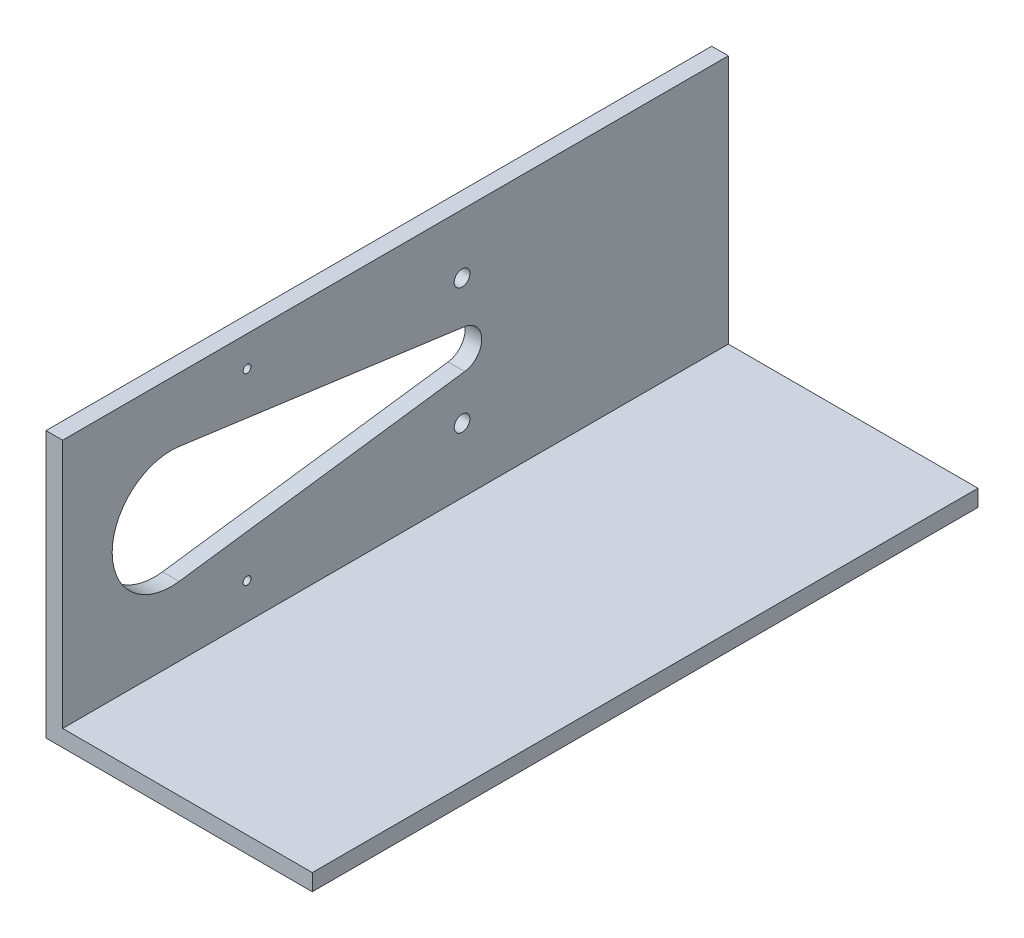
SolidWorks part; units mm, degrees
ref_plane "Alzado" through (0, 0, 0) normal (0, 0, 1) x (1, 0, 0)
ref_plane "Planta" through (0, 0, 0) normal (0, 1, 0) x (1, 0, 0)
ref_plane "Vista lateral" through (0, 0, 0) normal (1, 0, 0) x (0, 0, -1)
sketch "Croquis1" plane through (0, 0, 0) normal (0, 0, 1) x (1, 0, 0)
  line L0 (0, 101.6) -> (0, 0)
  line L1 (0, 0) -> (101.6, 0)
  line L2 (101.6, 0) -> (101.6, 6.35)
  line L3 (101.6, 6.35) -> (6.35, 6.35)
  line L4 (6.35, 6.35) -> (6.35, 101.6)
  line L5 (6.35, 101.6) -> (0, 101.6)
  dimension "D1" = 6.35
  dimension "D2" = 101.6
extrude "Saliente-Extruir1" add sketch "Croquis1" along normal blind 254
sketch "Croquis2" plane through (0, 0, 0) normal (-1, 0, 0) x (0, 0, 1)
  line L0 (101.6, 0) -> (101.6, 55) construction
  line L1 (254, 0) -> (0, 0) construction
  line L2 (0, 0) -> (0, -20) construction
  line L3 (0, -20) -> (254, -20) construction
  line L4 (254, -20) -> (254, 0) construction
  line L5 (101.6, 55) -> (212.6, 55) construction
  line L6 (100.5865, 62.4312) -> (209.5595, 77.2936)
  line L7 (100.5865, 47.5688) -> (209.5595, 32.7064)
  line L8 (101.6, 0) -> (101.6, -46.6) construction
  line L9 (101.6, -20) -> (101.6, -46.6) construction
  line L10 (0, 6.35) -> (254, 6.35) construction
  line L11 (0, 101.6) -> (0, 0) construction
  line L12 (254, 101.6) -> (254, 0) construction
  line L13 (183.64, 55) -> (183.64, 90) construction
  line L14 (101.6, 156.6) -> (254, 156.6) construction
  line L15 (254, 156.6) -> (254, -20) construction
  circle A0 centre (101.6, 55) radius 47 construction
  circle A1 centre (101.6, 55) radius 101.6 construction
  circle A2 centre (212.6, 55) radius 22.5
  circle A3 centre (101.6, 55) radius 7.5
  circle A4 centre (183.64, 90) radius 1.5
  circle A5 centre (183.64, 20) radius 1.5
  dimension "D1" = 94
  dimension "D3" = 203.2
  dimension "D6" = 45
  dimension "D7" = 15
  dimension "D12" = 3
  dimension "D2" = 55
  dimension "D4" = 20
  dimension "D5" = 111
  dimension "D8" = 6.35
  dimension "D9" = 101.6
  dimension "D10" = 82.04
  dimension "D11" = 35
extrude "Cortar-Extruir1" cut sketch "Croquis2" against normal blind 254 contours A3 | A3 L7 A2 L6 | A2 | A4 | A5
sketch "Croquis3" plane through (0, 0, 0) normal (-1, 0, 0) x (0, 0, 1)
  line L0 (101.6, 55) -> (101.6, 79) construction
  line L1 (101.6, 55) -> (0, 55) construction
  line L2 (0, 101.6) -> (0, 0) construction
  circle A0 centre (101.6, 79) radius 3
  circle A1 centre (101.6, 31) radius 3
  dimension "D2" = 6
  dimension "D1" = 24
extrude "Cortar-Extruir2" cut sketch "Croquis3" against normal through all
